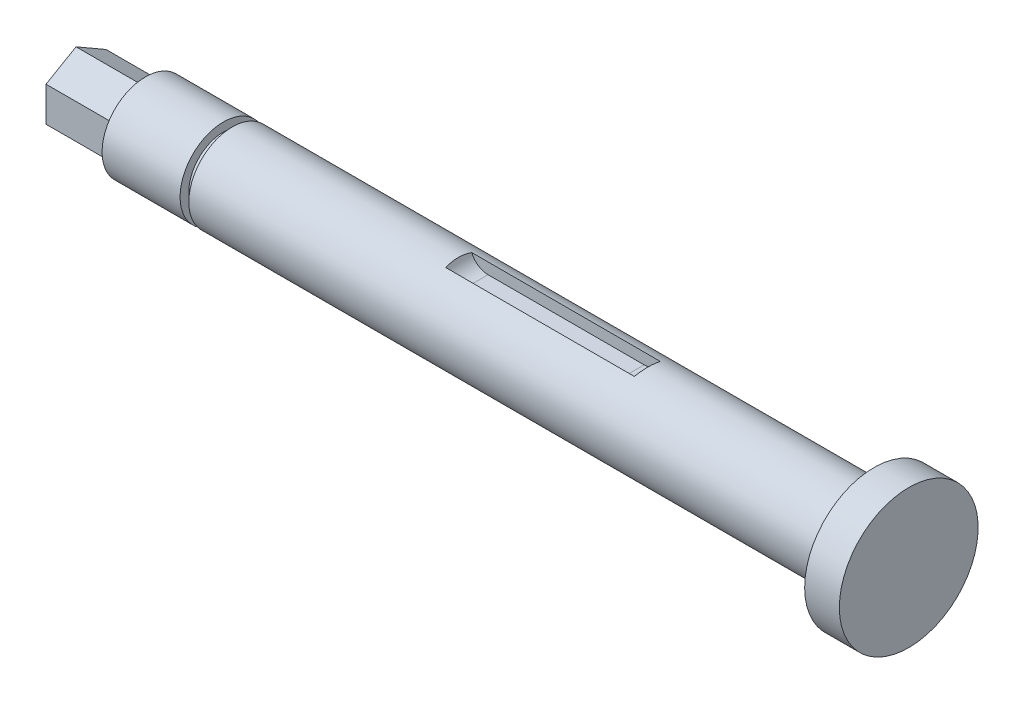
SolidWorks part; units mm, degrees
material "Chrome Stainless Steel"
ref_plane "Front Plane" through (0, 0, 0) normal (0, 0, 1) x (1, 0, 0)
ref_plane "Top Plane" through (0, 0, 0) normal (0, 1, 0) x (1, 0, 0)
ref_plane "Right Plane" through (0, 0, 0) normal (1, 0, 0) x (0, 0, -1)
sketch "Sketch2" plane through (0, 0, 0) normal (0, 0, 1) x (1, 0, 0)
  line L0 (-160.7251, 0) -> (201.3142, 0) construction
  line L1 (1316.2087, 0) -> (-1316.2087, 0) construction
  line L2 (0, 0) -> (0, 6.35)
  line L3 (0, 6.35) -> (12.7, 6.35)
  line L4 (12.7, 6.35) -> (12.7, 7.9375)
  line L5 (12.7, 7.9375) -> (26.9748, 7.9375)
  line L6 (26.9748, 7.9375) -> (26.9748, 6.3373)
  line L7 (26.9748, 6.3373) -> (28.575, 6.3373)
  line L8 (28.575, 6.3373) -> (28.575, 7.9375)
  line L9 (28.575, 7.9375) -> (146.05, 7.9375)
  line L10 (146.05, 7.9375) -> (146.05, 12.7)
  line L11 (146.05, 12.7) -> (152.4, 12.7)
  line L12 (152.4, 12.7) -> (152.4, 0)
  line L13 (152.4, 0) -> (0, 0)
  line L14 (0, -1132.7247) -> (0, 1132.7247) construction
  dimension "D1" = 12.7
  dimension "D2" = 1.6002
  dimension "D3" = 1.6002
  dimension "D4" = 133.35
  dimension "D5" = 6.35
  dimension "D6" = 117.475
  dimension "D7" = 15.875
  dimension "D8" = 12.7
  dimension "D9" = 25.4
  dimension "D10" = 152.4
revolve "Revolve1" add sketch "Sketch2" angle 360 about L0
sketch "Sketch3" plane through (0, 0, 0) normal (0, 0, 1) x (1, 0, 0)
  line L0 (69.85, 14.2875) -> (104.775, 14.2875)
  line L1 (104.775, 14.2875) -> (104.775, 8.7249)
  line L2 (101.6, 5.5499) -> (73.025, 5.5499)
  line L3 (69.85, 8.7249) -> (69.85, 14.2875)
  line L4 (146.05, 7.9375) -> (28.575, 7.9375) construction
  line L5 (101.6, 8.7249) -> (104.775, 8.7249) construction
  line L6 (69.85, 8.7249) -> (73.025, 8.7249) construction
  line L7 (101.6, 5.5499) -> (101.6, 8.7249) construction
  line L8 (73.025, 5.5499) -> (73.025, 8.7249) construction
  arc A0 (104.775, 8.7249) -> (101.6, 5.5499) centre (101.6, 8.7249) cw
  arc A1 (73.025, 5.5499) -> (69.85, 8.7249) centre (73.025, 8.7249) cw
  dimension "D1" = 3.175
  dimension "D2" = 34.925
  dimension "D3" = 6.35
  dimension "D4" = 2.3876
  dimension "D5" = 69.85
extrude "Cut-Extrude1" cut sketch "Sketch3" against normal mid plane 4.7625
sketch "Sketch6" plane through (0, 0, 0) normal (-1, 0, 0) x (0, 0, 1)
  line L1 (0, 6.35) -> (-5.4993, 3.175)
  line L2 (-5.4993, 3.175) -> (-5.4993, -3.175)
  line L3 (-5.4993, -3.175) -> (0, -6.35)
  line L4 (0, -6.35) -> (5.4993, -3.175)
  line L5 (5.4993, -3.175) -> (5.4993, 3.175)
  line L6 (5.4993, 3.175) -> (0, 6.35)
  circle A0 centre (0, 0) radius 6.35 construction
  circle A1 centre (0, 0) radius 6.35
  dimension "D3" = 12.7
  dimension "D1" = 6.35
  dimension "D2" = 5.4993
extrude "Cut-Extrude2" cut sketch "Sketch6" against normal up to surface (12.7 mm away) flip side to cut contours L1 L2 L3 L4 L5 L6 up to face at (12.7, 0, 6.35)
